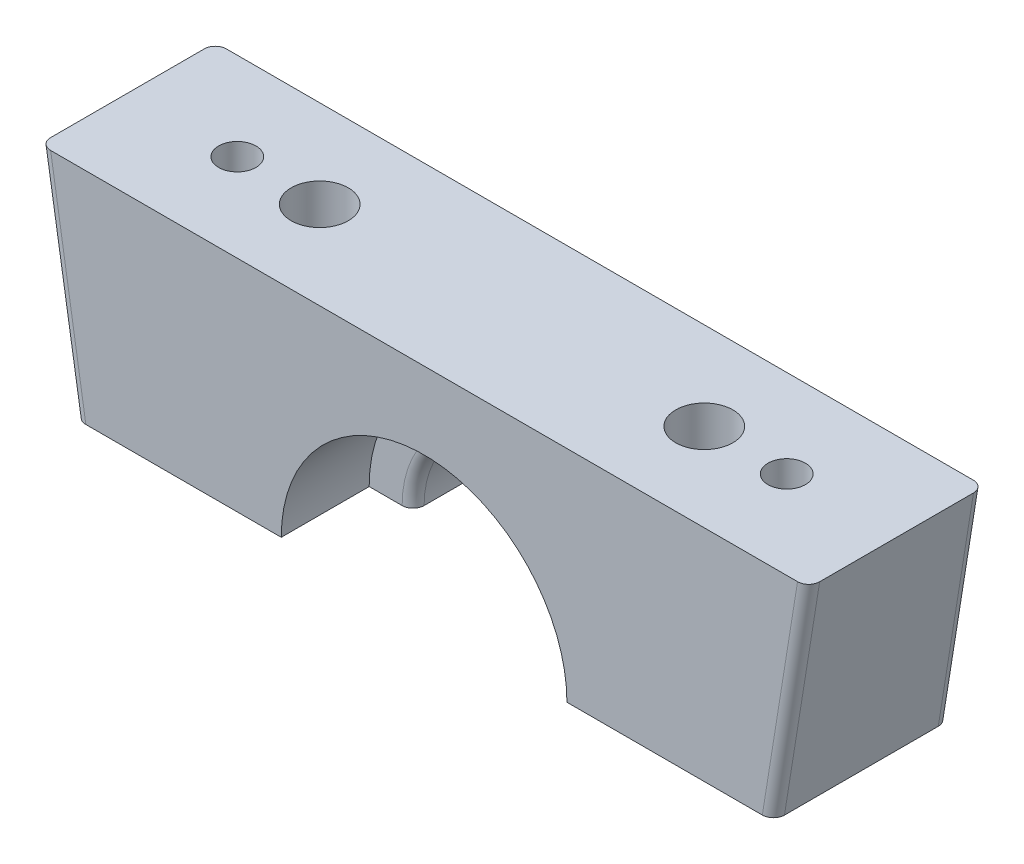
SolidWorks part; units mm, degrees
ref_plane "Płaszczyzna przednia" through (0, 0, 0) normal (0, 0, 1) x (1, 0, 0)
ref_plane "Płaszczyzna górna" through (0, 0, 0) normal (0, 1, 0) x (1, 0, 0)
ref_plane "Płaszczyzna prawa" through (0, 0, 0) normal (1, 0, 0) x (0, 0, -1)
sketch "Szkic1" plane through (0, 0, 0) normal (0, 0, 1) x (1, 0, 0)
  line L0 (0, 0) -> (35, 0)
  line L1 (35, 0) -> (31.7949, -20)
  line L2 (31.7949, -20) -> (0, -20)
  line L3 (0, -20) -> (0, 0)
  line L4 (35, 0) -> (60, 156) construction
  line L5 (35, 0) -> (60, 156) construction
  dimension "D2" = 20
extrude "Dodanie-wyciągnięcie1" add sketch "Szkic1" along normal mid plane 16
mirror "Lustro1" about plane through (0, -20, 8) normal (1, 0, 0) of "Dodanie-wyciągnięcie1"
sketch "Szkic2" plane through (0, 0, 8) normal (0, 0, 1) x (1, 0, 0)
  line L0 (-31.7949, -20) -> (31.7949, -20) construction
  line L1 (-13, -20) -> (13, -20)
  arc A0 (13, -20) -> (-13, -20) centre (0, -20) ccw
  dimension "D1" = 26
extrude "Wytnij-wyciągnięcie1" cut sketch "Szkic2" against normal blind 8
sketch "Szkic3" plane through (0, 0, 0) normal (0, 0, 1) x (1, 0, 0)
  line L1 (-13, -20) -> (13, -20)
  line L2 (-13, -20) -> (13, -20) construction
  arc A0 (9, -20) -> (-9, -20) centre (0, -20) ccw
  arc A1 (13, -20) -> (-13, -20) centre (0, -20) ccw
  arc A2 (13, -20) -> (-13, -20) centre (0, -20) ccw construction
  dimension "D1" = 0
  dimension "D2" = 4
extrude "Wytnij-wyciągnięcie2" cut sketch "Szkic3" against normal through all and the other way through all contours A0
hole_wizard "Pogłębienie stożkowe pod M3 wkręt do części metalowych z łbem soczewkowym1" positions "Szkic4" profile "Szkic5" countersink size "M3" standard "Ansi Metric" end condition up to next
sketch "Szkic4" plane through (0, -20, 0) normal (0, -1, 0) x (-1, 0, 0)
  point P0 (-25, 0)
  point P2 (25, 0)
  dimension "D1" = 50
  dimension "D2" = 25
sketch "Szkic5" plane through (25, -20, 0) normal (1, 0, 0) x (0, 0, -1)
  line L0 (0, 0) -> (0, 20)
  line L1 (0, 20) -> (1.7, 20)
  line L2 (1.7, 20) -> (1.7, 1.45)
  line L3 (1.7, 1.45) -> (3.15, 0)
  line L5 (3.15, 0) -> (0, 0)
  line L6 (-1.7, 1.45) -> (-3.15, 0) construction
  line L11 (0, -6.35) -> (0, 107.95) construction
  dimension "Średnica otworu na wylot" = 3.4
  dimension "Głębokość otworu na wylot" = 20
  dimension "Średnica zewnętrznego pogłębienia stożkowego" = 6.3
  dimension "Kąt zewnętrznego pogłębienia stożkowego" = 90
hole_wizard "Otwory ustalające Ø5.0mm1" positions "Szkic6" profile "Szkic7" hole size "Ø5.0" standard "Ansi Metric" end condition up to next
sketch "Szkic6" plane through (0, -20, 0) normal (0, -1, 0) x (-1, 0, 0)
  point P0 (-17.5, 0)
  point P2 (17.5, 0)
  dimension "D1" = 35
  dimension "D2" = 17.5
sketch "Szkic7" plane through (17.5, -20, 0) normal (1, 0, 0) x (0, 0, -1)
  line L0 (0, 0) -> (0, 20)
  line L1 (0, 20) -> (2.6, 20)
  line L2 (2.6, 20) -> (2.6, 0)
  line L5 (2.6, 0) -> (0, 0)
  line L11 (0, -6.35) -> (0, 107.95) construction
  dimension "Średnica otworu na wylot" = 5.2
  dimension "Głębokość otworu na wylot" = 20
sketch "Szkic8" plane through (0, -20, 0) normal (0, -1, 0) x (-1, 0, 0)
  circle A0 centre (17.5, 0) radius 2.6 construction
  circle A1 centre (-17.5, 0) radius 2.6 construction
  circle A4 centre (-17.5, 0) radius 2.6 construction
  circle A5 centre (17.5, 0) radius 2.6 construction
  circle A6 centre (17.5, 0) radius 3.25
  circle A7 centre (-17.5, 0) radius 3.25
  dimension "D1" = 6.5
extrude "Wytnij-wyciągnięcie3" cut sketch "Szkic8" against normal blind 10
fillet "Zaokrąglenie1" radius 1 6 edges at (0, -11, -8) (33.3974, -10, 8) (-33.3974, -10, -8) (-33.3974, -10, 8) (33.3974, -10, -8) (0, -11, 0)
equation "\"D2@Szkic4\"=\"D1@Szkic4\"/2"
equation "\"D2@Szkic6\"=\"D1@Szkic6\"/2"
